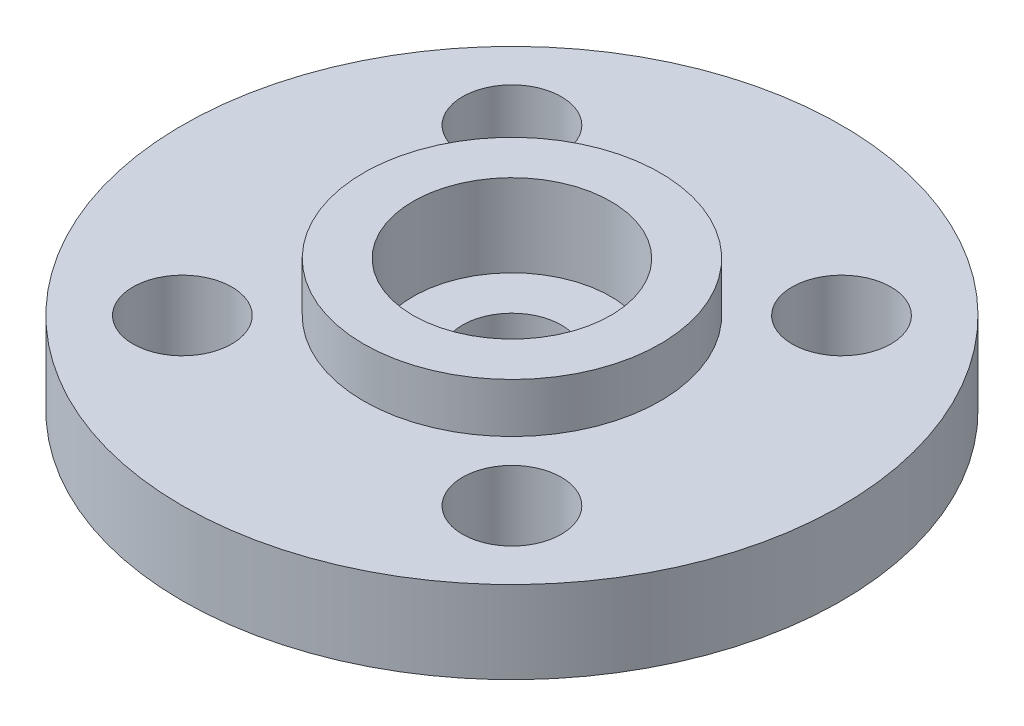
SolidWorks part; units mm, degrees
ref_plane "前视基准面" through (0, 0, 0) normal (0, 0, 1) x (1, 0, 0)
ref_plane "上视基准面" through (0, 0, 0) normal (0, 1, 0) x (1, 0, 0)
ref_plane "右视基准面" through (0, 0, 0) normal (1, 0, 0) x (0, 0, -1)
other "Configuration Table"
sketch "草图1" plane through (0, 0, 0) normal (0, 1, 0) x (1, 0, 0)
  line L1 (-5, -5) -> (5, -5)
  line L2 (-5, -5) -> (-5, 5)
  line L3 (-5, 5) -> (5, 5)
  line L4 (5, -5) -> (5, 5)
  line L5 (-5, -5) -> (5, 5) construction
  line L6 (-5, 5) -> (5, -5) construction
  circle A0 centre (0, 0) radius 10
  circle A1 centre (-5, 5) radius 1.5
  circle A2 centre (5, 5) radius 1.5
  circle A3 centre (5, -5) radius 1.5
  circle A4 centre (-5, -5) radius 1.5
  circle A5 centre (0, 0) radius 2.331
  dimension "D1" = 20
  dimension "D4" = 3
  dimension "D2" = 10
  dimension "D3" = 10
  dimension "D5" = 4
extrude "凸台-拉伸2" add sketch "草图1" along normal blind 2.5 contours A0 A4 L2 A1 L3 A2 L4 A3 L1 | A4 L1 A3 L4 A2 L3 A1 L2 A5
sketch "草图2" plane through (0, 2.5, 0) normal (0, 1, 0) x (1, 0, 0)
  circle A0 centre (0, 0) radius 3
  dimension "D1" = 6
extrude "切除-拉伸1" cut sketch "草图2" against normal blind 1
sketch "草图3" plane through (0, 1.5, 0) normal (0, 1, 0) x (1, 0, 0)
  circle A0 centre (0, 0) radius 1.5
  dimension "D1" = 3
extrude "切除-拉伸3" cut sketch "草图3" against normal through all
sketch "草图4" plane through (0, 2.5, 0) normal (0, 1, 0) x (1, 0, 0)
  circle A0 centre (0, 0) radius 3
  circle A1 centre (0, 0) radius 4.5
  dimension "D1" = 9
extrude "凸台-拉伸3" add sketch "草图4" along normal blind 1.5
